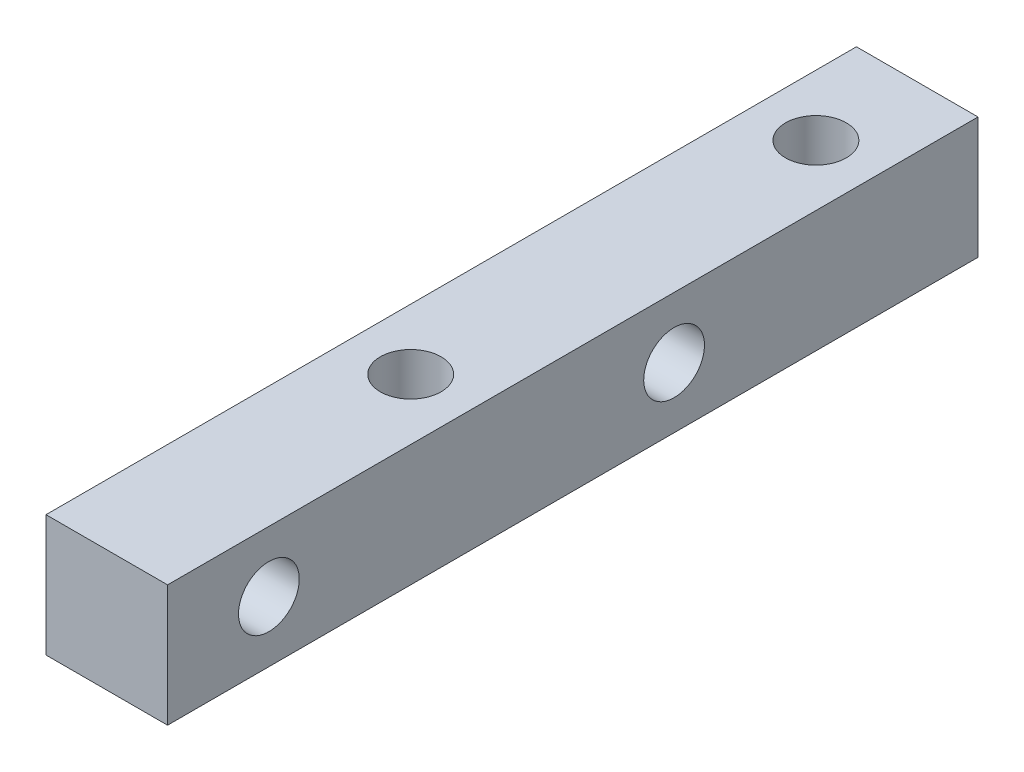
SolidWorks part; units mm, degrees
material "AISI 4130 钢，正火温度为 870C"
ref_plane "前视基准面" through (0, 0, 0) normal (0, 0, 1) x (1, 0, 0)
ref_plane "上视基准面" through (0, 0, 0) normal (0, 1, 0) x (1, 0, 0)
ref_plane "右视基准面" through (0, 0, 0) normal (1, 0, 0) x (0, 0, -1)
sketch "草图1" plane through (0, 0, 0) normal (0, 0, 1) x (1, 0, 0)
  line L1 (-3, 3) -> (3, 3)
  line L2 (-3, 3) -> (-3, -3)
  line L3 (-3, -3) -> (3, -3)
  line L4 (3, 3) -> (3, -3)
  line L5 (-3, 3) -> (3, -3) construction
  line L6 (-3, -3) -> (3, 3) construction
  point P0 (0, 0)
  dimension "D1" = 6
  dimension "D2" = 6
extrude "凸台-拉伸1" add sketch "草图1" along normal mid plane 40
sketch "草图2" plane through (3, 0, 0) normal (1, 0, 0) x (0, 0, -1)
  line L0 (-20, -3) -> (-20, 3) construction
  circle A0 centre (-15, 0) radius 1.5
  circle A1 centre (5, 0) radius 1.5
  dimension "D1" = 3
  dimension "D2" = 20
  dimension "D3" = 5
extrude "切除-拉伸1" cut sketch "草图2" against normal up to next
sketch "草图3" plane through (0, 3, 0) normal (0, 1, 0) x (1, 0, 0)
  line L0 (3, 20) -> (-3, 20) construction
  circle A0 centre (0, 15) radius 1.5
  circle A1 centre (0, -5) radius 1.5
  dimension "D1" = 20
  dimension "D2" = 5
  dimension "D3" = 3
extrude "切除-拉伸2" cut sketch "草图3" against normal up to next
